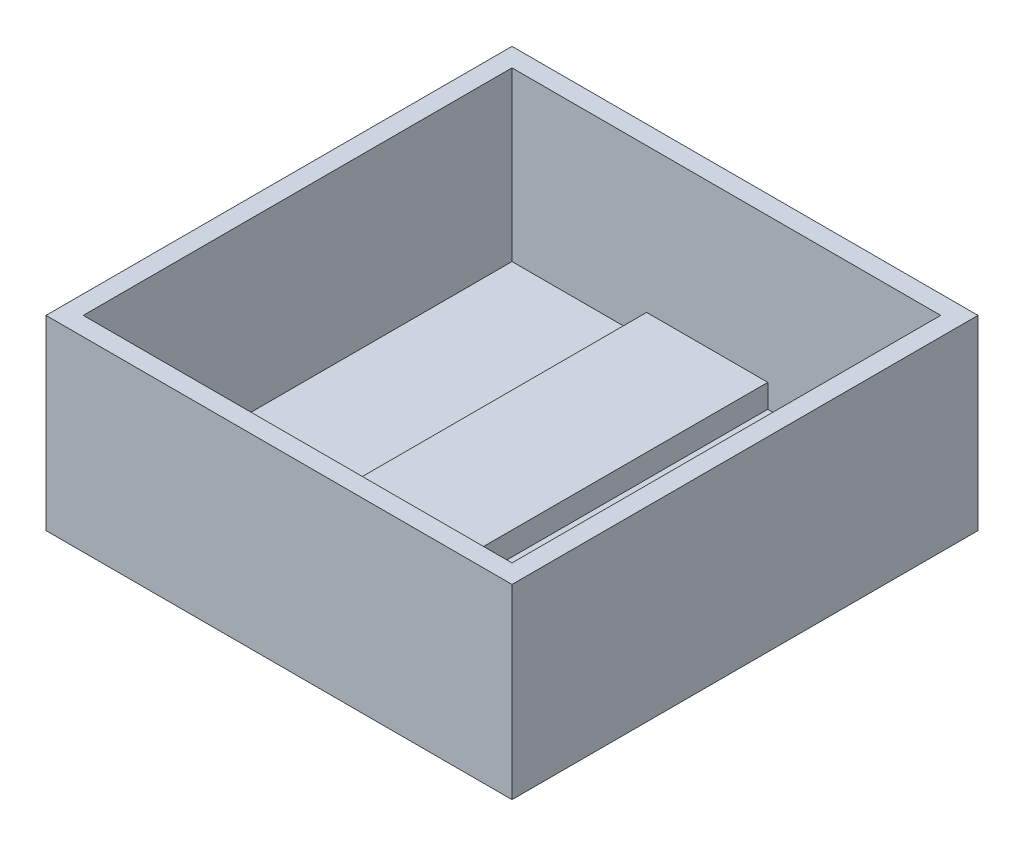
SolidWorks part; units mm, degrees
ref_plane "Front Plane" through (0, 0, 0) normal (0, 0, 1) x (1, 0, 0)
ref_plane "Top Plane" through (0, 0, 0) normal (0, 1, 0) x (1, 0, 0)
ref_plane "Right Plane" through (0, 0, 0) normal (1, 0, 0) x (0, 0, -1)
sketch "Sketch1" plane through (0, 0, 0) normal (0, 1, 0) x (1, 0, 0)
  line L1 (-50.5712, -39.9173) -> (49.4288, -39.9173)
  line L2 (-50.5712, -39.9173) -> (-50.5712, 60.0827)
  line L3 (-50.5712, 60.0827) -> (49.4288, 60.0827)
  line L4 (49.4288, -39.9173) -> (49.4288, 60.0827)
  dimension "D1" = 100
  dimension "D2" = 100
extrude "Boss-Extrude1" add sketch "Sketch1" along normal blind 40
sketch "Sketch2" plane through (0, 40, 0) normal (0, 1, 0) x (1, 0, 0)
  line L0 (49.4288, 60.0827) -> (-50.5712, 60.0827) construction
  line L1 (-46.5712, 56.0827) -> (45.4288, 56.0827)
  line L2 (-46.5712, 56.0827) -> (-46.5712, -35.9173)
  line L3 (-46.5712, -35.9173) -> (45.4288, -35.9173)
  line L4 (45.4288, 56.0827) -> (45.4288, -35.9173)
  line L5 (-50.5712, -39.9173) -> (49.4288, -39.9173) construction
  line L6 (-50.5712, 60.0827) -> (-50.5712, -39.9173) construction
  line L7 (49.4288, -39.9173) -> (49.4288, 60.0827) construction
  dimension "D1" = 4
  dimension "D2" = 4
  dimension "D3" = 4
  dimension "D4" = 4
extrude "Cut-Extrude1" cut sketch "Sketch2" against normal blind 36
sketch "Sketch3" plane through (0, 4, 0) normal (0, 1, 0) x (1, 0, 0)
  line L1 (49.4288, 60.0827) -> (-50.5712, 60.0827) construction
  line L2 (-17.678, 60.0827) -> (8.322, 60.0827)
  line L3 (-17.678, 60.0827) -> (-17.678, -9.9173)
  line L4 (-17.678, -9.9173) -> (8.322, -9.9173)
  line L5 (8.322, 60.0827) -> (8.322, -9.9173)
  dimension "D1" = 26
  dimension "D2" = 70
extrude "Boss-Extrude2" add sketch "Sketch3" along normal blind 5
